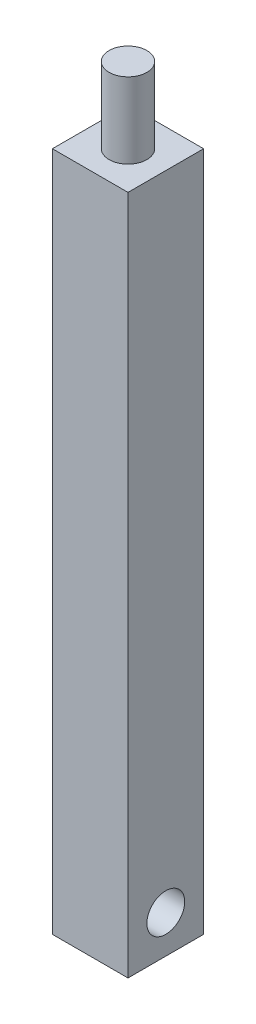
SolidWorks part; units mm, degrees
material "6061 Alloy"
ref_plane "Front Plane" through (0, 0, 0) normal (0, 0, 1) x (1, 0, 0)
ref_plane "Top Plane" through (0, 0, 0) normal (0, 1, 0) x (1, 0, 0)
ref_plane "Right Plane" through (0, 0, 0) normal (1, 0, 0) x (0, 0, -1)
sketch "Sketch1" plane through (0, 0, 0) normal (0, 1, 0) x (1, 0, 0)
  line L1 (-5, 5) -> (5, 5)
  line L2 (-5, 5) -> (-5, -5)
  line L3 (-5, -5) -> (5, -5)
  line L4 (5, 5) -> (5, -5)
  line L5 (-5, 5) -> (5, -5) construction
  line L6 (-5, -5) -> (5, 5) construction
  point P0 (0, 0)
  dimension "D1" = 10
  dimension "D2" = 10
extrude "Boss-Extrude1" add sketch "Sketch1" along normal blind 90
sketch "Sketch2" plane through (0, 90, 0) normal (0, 1, 0) x (1, 0, 0)
  circle A0 centre (0, 0) radius 2.5
  dimension "D1" = 5
extrude "Boss-Extrude2" add sketch "Sketch2" along normal blind 10
sketch "Sketch3" plane through (5, 0, 0) normal (1, 0, 0) x (0, 0, -1)
  line L0 (-5, 0) -> (5, 0) construction
  circle A0 centre (0, 5) radius 2.5
  dimension "D1" = 5
  dimension "D2" = 5
extrude "Cut-Extrude1" cut sketch "Sketch3" against normal through all
